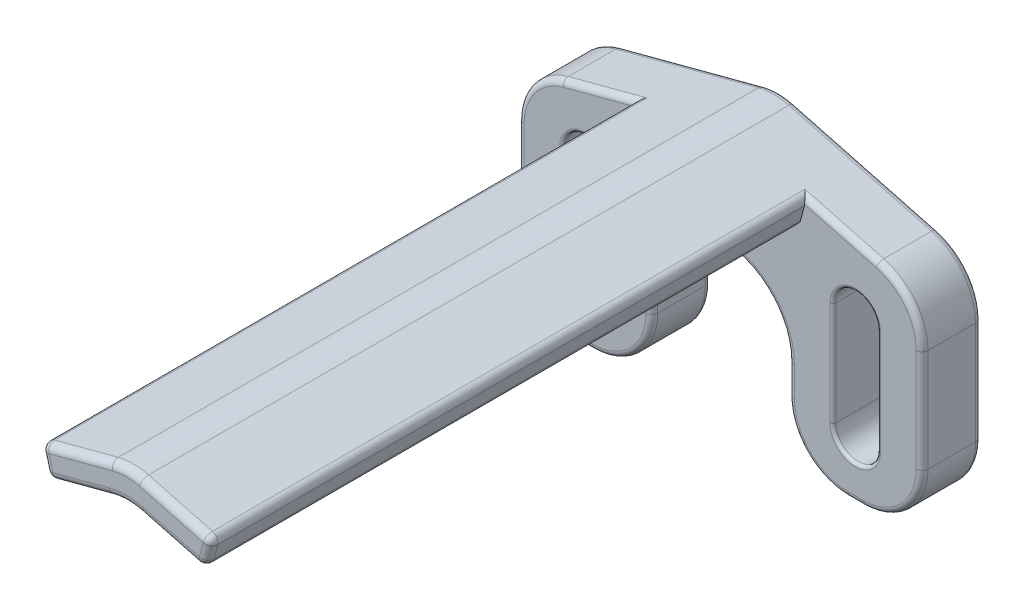
SolidWorks part; units mm, degrees
ref_plane "Front Plane" through (0, 0, 0) normal (0, 0, 1) x (1, 0, 0)
ref_plane "Top Plane" through (0, 0, 0) normal (0, 1, 0) x (1, 0, 0)
ref_plane "Right Plane" through (0, 0, 0) normal (1, 0, 0) x (0, 0, -1)
sketch "Sketch1" plane through (0, 0, 0) normal (0, 0, 1) x (1, 0, 0)
  line L0 (-17.272, -5.08) -> (-17.272, -12.7)
  line L1 (-17.272, -5.08) -> (17.272, -5.08) construction
  line L2 (-17.272, -5.08) -> (-17.272, 5.08)
  line L3 (-17.272, 5.08) -> (17.272, 5.08) construction
  line L4 (17.272, -5.08) -> (17.272, 5.08)
  line L5 (-17.272, -5.08) -> (17.272, 5.08) construction
  line L6 (-17.272, 5.08) -> (17.272, -5.08) construction
  line L7 (-17.272, -12.7) -> (-5.842, -12.7)
  line L8 (-5.842, -12.7) -> (-5.842, -5.08)
  line L10 (5.842, -5.08) -> (5.842, -12.7)
  line L11 (5.842, -12.7) -> (17.272, -12.7)
  line L12 (17.272, -12.7) -> (17.272, -5.08)
  line L13 (0, 0.762) -> (0, 9.652) construction
  line L14 (0, 9.652) -> (-17.272, 5.08)
  line L15 (0, 9.652) -> (17.272, 5.08)
  arc A0 (5.842, -5.08) -> (-5.842, -5.08) centre (0, -5.08) ccw
  point P0 (0, 0)
  dimension "D1" = 10.16
  dimension "D2" = 34.544
  dimension "D3" = 17.78
  dimension "D4" = 11.684
  dimension "D5" = 8.89
extrude "Boss-Extrude1" add sketch "Sketch1" along normal blind 5.08 contours L4 L15 L14 L2 L0 L7 L8 A0 L10 L11 L12
fillet "Fillet1" radius 5.08 4 edges at (17.272, -12.7, 2.54) (5.842, -12.7, 2.54) (-5.842, -12.7, 2.54) (-17.272, -12.7, 2.54)
sketch "Sketch2" plane through (0, 0, 5.08) normal (0, 0, 1) x (1, 0, 0)
  line L0 (0, 9.652) -> (0, -7.874) construction
  line L1 (0, -7.874) -> (11.557, -7.874) construction
  line L2 (0, -7.874) -> (-11.557, -7.874) construction
  line L3 (0, 1.016) -> (-11.557, 1.016) construction
  line L4 (0, 1.016) -> (11.557, 1.016) construction
  line L5 (-11.557, 1.016) -> (-11.557, -7.874) construction
  line L6 (-9.652, 1.016) -> (-9.652, -7.874)
  line L7 (-13.462, 1.016) -> (-13.462, -7.874)
  line L8 (11.557, 1.016) -> (11.557, -7.874) construction
  line L9 (13.462, 1.016) -> (13.462, -7.874)
  line L10 (9.652, 1.016) -> (9.652, -7.874)
  line L11 (0, 0.762) -> (17.272, 0.762) construction
  line L12 (17.272, -7.62) -> (17.272, 5.08) construction
  arc A0 (-9.652, 1.016) -> (-13.462, 1.016) centre (-11.557, 1.016) ccw
  arc A1 (-13.462, -7.874) -> (-9.652, -7.874) centre (-11.557, -7.874) ccw
  arc A2 (13.462, 1.016) -> (9.652, 1.016) centre (11.557, 1.016) ccw
  arc A3 (9.652, -7.874) -> (13.462, -7.874) centre (11.557, -7.874) ccw
  arc A4 (5.842, -5.08) -> (-5.842, -5.08) centre (0, -5.08) ccw construction
  point P3 (-11.557, -3.429)
  point P13 (11.557, -3.429)
  dimension "D1" = 23.114
  dimension "D2" = 3.81
  dimension "D3" = 3.81
  dimension "D4" = 0.254
  dimension "D5" = 8.89
extrude "Cut-Extrude1" cut sketch "Sketch2" against normal through all both and the other way through all
sketch "Sketch3" plane through (0, 0, 5.08) normal (0, 0, 1) x (1, 0, 0)
  line L2 (-6.7163, 5.2467) -> (0, 7.0245)
  line L3 (0, 7.0245) -> (6.7163, 5.2467)
  line L6 (0, 9.652) -> (-7.3663, 7.7021)
  line L7 (0, 9.652) -> (-17.272, 5.08) construction
  line L8 (-7.3663, 7.7021) -> (-6.7163, 5.2467)
  line L9 (0, 9.652) -> (7.3663, 7.7021)
  line L10 (0, 9.652) -> (17.272, 5.08) construction
  line L11 (7.3663, 7.7021) -> (6.7163, 5.2467)
  line L12 (0, 9.652) -> (0, 7.0245) construction
  dimension "D1" = 2.54
  dimension "D2" = 7.62
extrude "Boss-Extrude2" add sketch "Sketch3" along normal blind 50.8 contours L8 L2 L3 L11 L9 L6
fillet "Fillet2" radius 5.08 4 edges at (0, 9.652, 27.94) (0, 7.0245, 30.48) (17.272, 5.08, 2.54) (-17.272, 5.08, 2.54)
fillet "Fillet3" radius 0.635 4 edges at (7.3663, 7.7021, 30.48) (-7.3663, 7.7021, 30.48) (6.7163, 5.2467, 30.48) (-6.7163, 5.2467, 30.48)
fillet "Fillet4" radius 0.635 12 edges at (0, 9.477, 55.88) (4.0262, 8.5862, 55.88) (7.1389, 7.5699, 55.88) (7.0413, 6.4744, 55.88) (6.5841, 5.4741, 55.88) (3.7012, 6.0448, 55.88) (0, 6.8496, 55.88) (-3.7012, 6.0448, 55.88) (-6.5841, 5.4741, 55.88) (-7.0413, 6.4744, 55.88) (-7.1389, 7.5699, 55.88) (-4.0262, 8.5862, 55.88)
fillet "Fillet5" radius 0.508 31 edges at (-17.272, -3.2251, 0) (-15.7841, -11.2121, 0) (-11.557, -12.7, 0) (-7.3299, -11.2121, 0) (-5.842, -6.35, 0) (0, 0.762, 0) (5.842, -6.35, 0) (7.3299, -11.2121, 0) (11.557, -12.7, 0) (15.7841, -11.2121, 0) (17.272, -3.2251, 0) (16.2175, 4.2684, 0) (7.3959, 7.6943, 0) (0, 9.477, 0) (-7.3959, 7.6943, 0) (10.1222, 6.9726, 5.08) (16.2175, 4.2684, 5.08) (17.272, -3.2251, 5.08) (15.7841, -11.2121, 5.08) (11.557, -12.7, 5.08) (7.3299, -11.2121, 5.08) (5.842, -6.35, 5.08) (-10.1222, 6.9726, 5.08) (-16.2175, 4.2684, 5.08) (-17.272, -3.2251, 5.08) (-15.7841, -11.2121, 5.08) (-11.557, -12.7, 5.08) (-7.3299, -11.2121, 5.08) (-5.842, -6.35, 5.08) (-16.2175, 4.2684, 0) (0, 0.762, 5.08)
fillet "Fillet6" radius 0.254 16 edges at (-11.557, -9.779, 5.08) (-13.462, -3.429, 5.08) (-11.557, 2.921, 5.08) (11.557, -9.779, 5.08) (9.652, -3.429, 5.08) (11.557, 2.921, 5.08) (-11.557, -9.779, 0) (-13.462, -3.429, 0) (-11.557, 2.921, 0) (11.557, 2.921, 0) (13.462, -3.429, 0) (11.557, -9.779, 0) (-9.652, -3.429, 5.08) (13.462, -3.429, 5.08) (-9.652, -3.429, 0) (9.652, -3.429, 0)
equation "\"D3@Sketch2\"=\"D2@Sketch2\""
